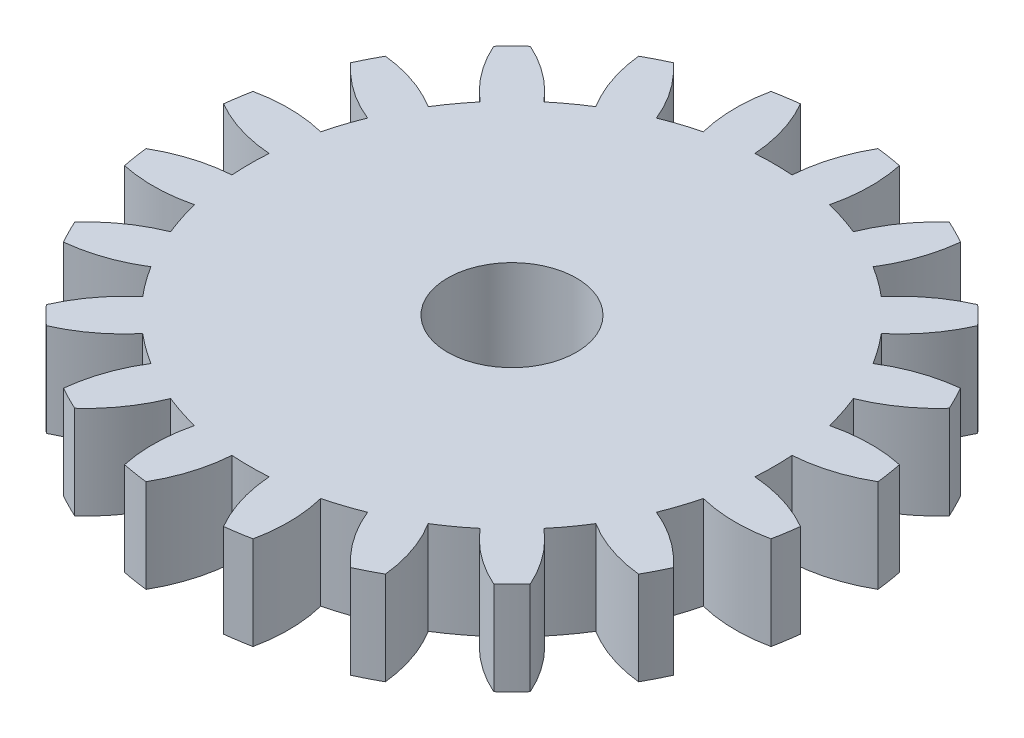
SolidWorks part; units mm, degrees
ref_plane "Front Plane" through (0, 0, 0) normal (0, 0, 1) x (1, 0, 0)
ref_plane "Top Plane" through (0, 0, 0) normal (0, 1, 0) x (1, 0, 0)
ref_plane "Right Plane" through (0, 0, 0) normal (1, 0, 0) x (0, 0, -1)
sketch "Sketch1" plane through (0, 0, 0) normal (0, 1, 0) x (1, 0, 0)
  circle A0 centre (0, 0) radius 8.255
  dimension "D1" = 16.51
extrude "Boss-Extrude1" add sketch "Sketch1" along normal blind 2.3368 contours A0
sketch "Sketch2" plane through (0, 2.3368, 0) normal (0, 1, 0) x (1, 0, 0)
  circle A0 centre (0, 0) radius 1.6129
  dimension "D1" = 3.2258
extrude "Cut-Extrude1" cut sketch "Sketch2" against normal through all
sketch "Sketch3" plane through (0, 2.3368, 0) normal (0, 1, 0) x (1, 0, 0)
  line L1 (0, 0) -> (0, 12.3699) construction
  line L3 (1.4263, 8.8274) -> (-1.4263, 8.8274)
  arc A1 (0.4655, 6.5494) -> (-0.4655, 6.5494) centre (0, 0) ccw
  arc A3 (0.4655, 6.5494) -> (1.4263, 8.8274) centre (4.2908, 6.2775) cw
  arc A4 (-0.4655, 6.5494) -> (-1.4263, 8.8274) centre (-4.2908, 6.2775) ccw
  point P7 (-0.7625, 8.3198)
  point P9 (0.7625, 8.3198)
  point P13 (0, 8.8274)
extrude "Cut-Extrude6" cut sketch "Sketch3" against normal through all contours A1 A4 L3 A3
pattern_circular "CirPattern1" count 20 over 360 about axis through (0, 0, 0) along (0, 1, 0) of "Cut-Extrude6"
